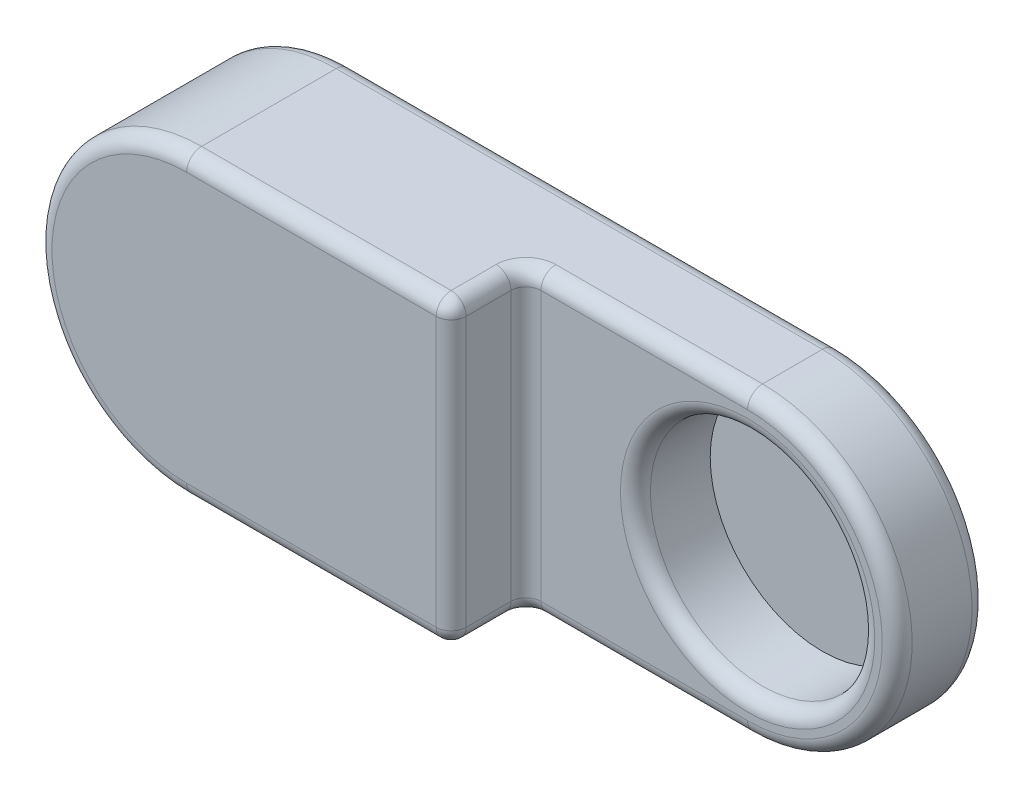
SolidWorks part; units mm, degrees
material "AISI 4340 Stahllegierung"
ref_plane "Ebene vorne" through (0, 0, 0) normal (0, 0, 1) x (1, 0, 0)
ref_plane "Ebene oben" through (0, 0, 0) normal (0, 1, 0) x (1, 0, 0)
ref_plane "Ebene rechts" through (0, 0, 0) normal (1, 0, 0) x (0, 0, -1)
sketch "Skizze1" plane through (0, 0, 0) normal (0, 0, 1) x (1, 0, 0)
  line L2 (0, 100) -> (325, 100)
  line L4 (0, -100) -> (325, -100)
  line L6 (-96.8191, -25.0213) -> (100, -100) construction
  line L7 (-96.8191, 25.0213) -> (100, 100) construction
  circle A0 centre (0, 0) radius 75
  circle A1 centre (325, 0) radius 75
  arc A2 (0, 100) -> (0, -100) centre (0, 0) ccw
  arc A4 (325, -100) -> (325, 100) centre (325, 0) ccw
  point P2 (-161.3701, 19.1297)
  dimension "D5" = 150
  dimension "D2" = 200
  dimension "D1" = 325
  dimension "D4" = 162.5
  dimension "D6" = 100
extrude "Aufsatz-Linear austragen1" add sketch "Skizze1" along normal blind 60
sketch "Skizze2" plane through (0, 0, 60) normal (0, 0, 1) x (1, 0, 0)
  line L0 (0, 100) -> (176.831, 100)
  line L2 (176.831, 100) -> (176.831, -100)
  line L4 (176.831, -100) -> (0, -100)
  arc A1 (0, 100) -> (0, -100) centre (0, 0) ccw
  arc A2 (0, 100) -> (0, -100) centre (0, 0) ccw construction
extrude "Aufsatz-Linear austragen2" add sketch "Skizze2" along normal blind 50
sketch "Skizze4" plane through (0, 0, 0) normal (0, 0, -1) x (-1, 0, 0)
  circle A0 centre (-324.9228, 0.0334) radius 74.9159
extrude "Aufsatz-Linear austragen3" add sketch "Skizze4" against normal blind 10 separate body
fillet "Verrundung7" radius 10 16 edges at (75, 0, 0) (162.5, 100, 0) (-100, 0, 0) (162.5, -100, 0) (425, 0, 0) (400, 0, 60) (250.9155, -100, 60) (250.9155, 100, 60) (425, 0, 60) (176.831, 100, 85) (176.831, -100, 85) (176.831, 0, 60) (88.4155, 100, 110) (88.4155, -100, 110) (176.831, 0, 110) (-100, 0, 110)
equation "\"L2\"=325"
equation "\"D1@Skizze1\"=\"L2\""
equation "\"D4@Skizze1\"=\"L2\"/2"
equation "\"Breite_ZweitesGlied\"= 200"
equation "\"D2@Skizze1\"=\"Breite_ZweitesGlied\""
equation "\"D5@Skizze1\"=\"Breite_ZweitesGlied\"-50"
equation "\"D6@Skizze1\"=\"Breite_ZweitesGlied\"/2"
equation "\"Höhe_ZweitesGlied\"=60"
equation "\"D1@Aufsatz-Linear austragen1\"=\"Höhe_ZweitesGlied\""
